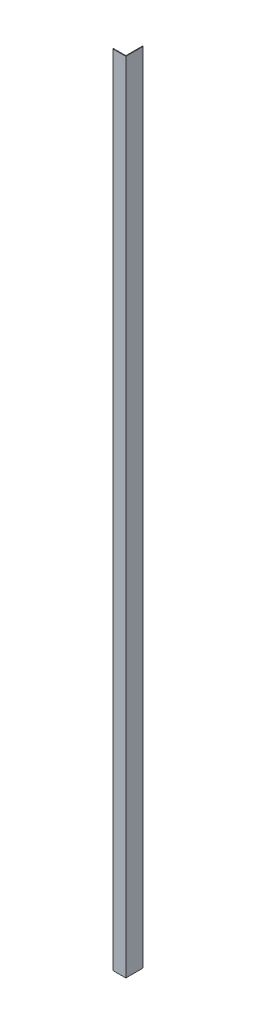
SolidWorks part; units mm, degrees
ref_plane "Front Plane" through (0, 0, 0) normal (0, 0, 1) x (1, 0, 0)
ref_plane "Top Plane" through (0, 0, 0) normal (0, 1, 0) x (1, 0, 0)
ref_plane "Right Plane" through (0, 0, 0) normal (1, 0, 0) x (0, 0, -1)
other "Configuration Table"
sketch "Sketch1" plane through (0, 0, 0) normal (0, 1, 0) x (1, 0, 0)
  line L0 (0, -40) -> (0, -38.5)
  line L1 (0, -38.5) -> (28.5, -38.5)
  line L2 (28.5, -38.5) -> (28.5, 0)
  line L3 (28.5, 0) -> (30, 0)
  line L4 (30, 0) -> (30, -40)
  line L5 (30, -40) -> (0, -40)
extrude "PRESS_sove_sol_1" add sketch "Sketch1" along normal blind 1850 from offset 120 separate body
